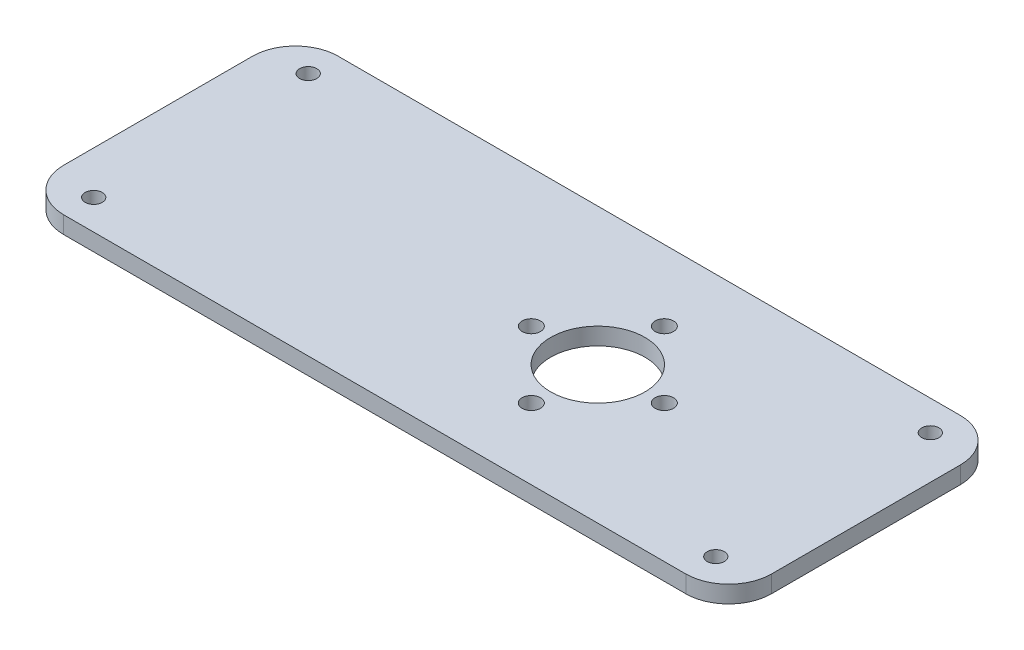
SolidWorks part; units mm, degrees
ref_plane "Front" through (0, 0, 0) normal (0, 0, 1) x (1, 0, 0)
ref_plane "Top" through (0, 0, 0) normal (0, 1, 0) x (1, 0, 0)
ref_plane "Right" through (0, 0, 0) normal (1, 0, 0) x (0, 0, -1)
sketch "草图1" plane through (0, 0, 0) normal (0, 1, 0) x (1, 0, 0)
  line L0 (0, 32) -> (165, 32) construction
  line L1 (0, 0) -> (165, 0)
  line L2 (0, 0) -> (0, 64)
  line L3 (0, 64) -> (165, 64)
  line L4 (165, 0) -> (165, 64)
  line L5 (82.5, 64) -> (82.5, 0) construction
  line L7 (155, 7) -> (10, 7) construction
  line L8 (155, 7) -> (155, 57) construction
  line L9 (155, 57) -> (10, 57) construction
  line L10 (10, 7) -> (10, 57) construction
  line L11 (155, 7) -> (10, 57) construction
  line L12 (155, 57) -> (10, 7) construction
  circle A0 centre (10, 57) radius 2
  circle A1 centre (155, 57) radius 2
  circle A2 centre (155, 7) radius 2
  circle A3 centre (10, 7) radius 2
  circle A4 centre (82.5, 32) radius 11 construction
  circle A5 centre (82.5, 32) radius 15.5 construction
  circle A6 centre (82.5, 47.5) radius 2.15 construction
  circle A7 centre (98, 32) radius 2.15 construction
  circle A8 centre (82.5, 16.5) radius 2.15 construction
  circle A9 centre (67, 32) radius 2.15 construction
  circle A10 centre (102.5, 32) radius 15.5 construction
  circle A11 centre (102.5, 47.5) radius 2.15
  circle A12 centre (87, 32) radius 2.15
  circle A13 centre (102.5, 16.5) radius 2.15
  circle A14 centre (118, 32) radius 2.15
  circle A15 centre (102.5, 32) radius 11
  point P9 (82.5, 32)
  point P32 (82.5, 32)
  dimension "D5" = 4
  dimension "D6" = 4
  dimension "D7" = 4
  dimension "D8" = 4
  dimension "D9" = 22
  dimension "D10" = 31
  dimension "D11" = 4
  dimension "D12" = 31
  dimension "D13" = 20
  dimension "D14" = 4.3
  dimension "D15" = 4.3
  dimension "D16" = 4.3
  dimension "D17" = 4.3
  dimension "D18" = 4.3
  dimension "D19" = 22
  dimension "D1" = 64
  dimension "D2" = 165
  dimension "D3" = 50
  dimension "D4" = 145
extrude "凸台-拉伸1" add sketch "草图1" along normal blind 4
fillet "圆角1" radius 10 4 edges at (0, 2, -64) (0, 2, 0) (165, 2, 0) (165, 2, -64)
